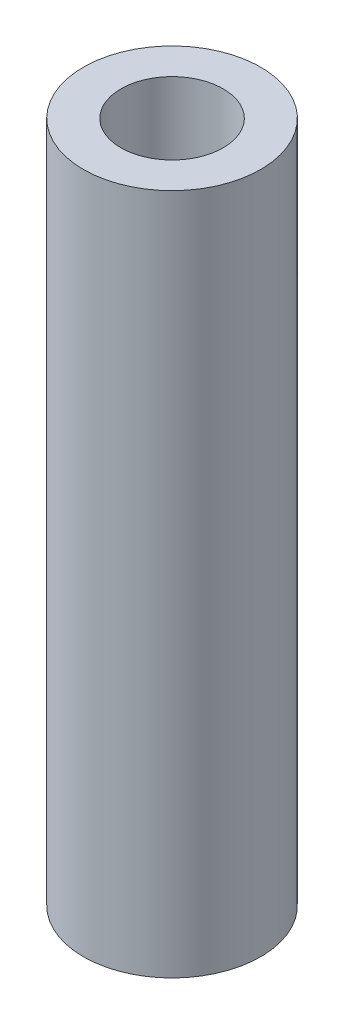
SolidWorks part; units mm, degrees
material "1060 合金"
ref_plane "前视基准面" through (0, 0, 0) normal (0, 0, 1) x (1, 0, 0)
ref_plane "上视基准面" through (0, 0, 0) normal (0, 1, 0) x (1, 0, 0)
ref_plane "右视基准面" through (0, 0, 0) normal (1, 0, 0) x (0, 0, -1)
other "Configuration Table"
sketch "草图1" plane through (0, 0, 0) normal (0, 1, 0) x (1, 0, 0)
  circle A0 centre (0, 0) radius 2.6
  circle A1 centre (0, 0) radius 1.5
  dimension "D1" = 3
  dimension "5" = 5.2
extrude "凸台-拉伸1" add sketch "草图1" along normal blind 20
